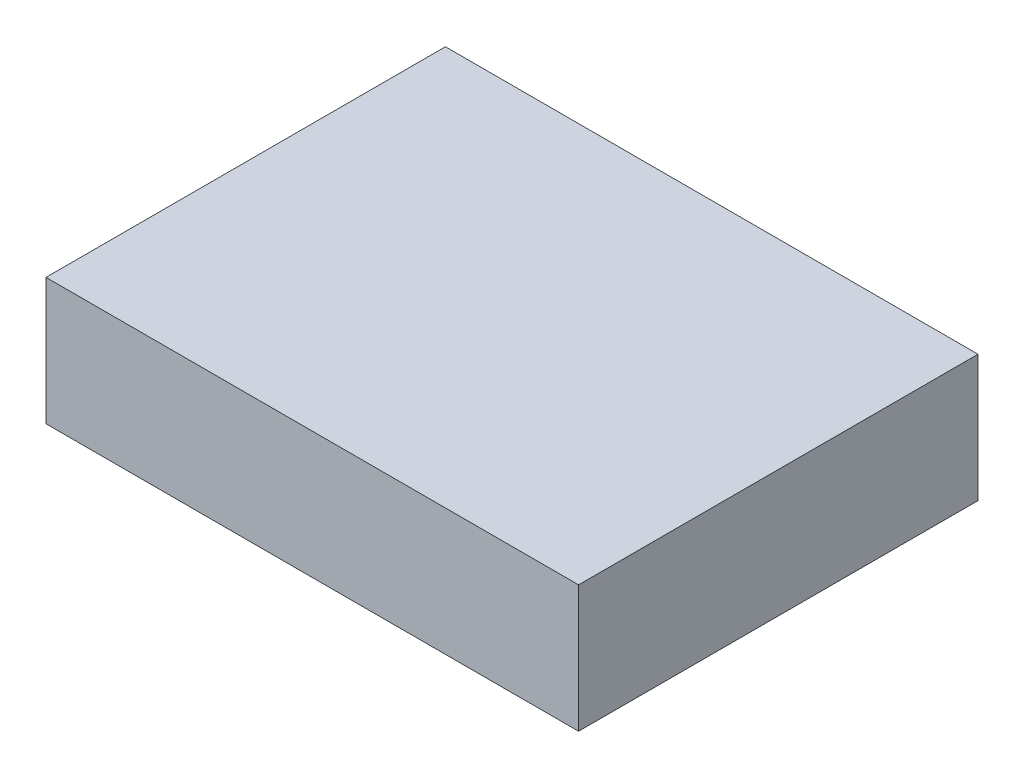
SolidWorks part; units mm, degrees
ref_plane "前视基准面" through (0, 0, 0) normal (0, 0, 1) x (1, 0, 0)
ref_plane "上视基准面" through (0, 0, 0) normal (0, 1, 0) x (1, 0, 0)
ref_plane "右视基准面" through (0, 0, 0) normal (1, 0, 0) x (0, 0, -1)
other "Configuration Table"
sketch "草图1" plane through (0, 0, 0) normal (0, 1, 0) x (1, 0, 0)
  line L1 (0, 0) -> (210, 0)
  line L2 (0, 0) -> (0, 157.5)
  line L3 (0, 157.5) -> (210, 157.5)
  line L4 (210, 0) -> (210, 157.5)
  line L5 (34.0565, 157.5) -> (59.0565, 157.5)
  line L6 (34.0565, 157.5) -> (34.0565, 172.5)
  line L7 (44.0565, 182.5) -> (49.0565, 182.5)
  line L8 (59.0565, 157.5) -> (59.0565, 172.5)
  line L9 (156.4911, 157.5) -> (181.4911, 157.5)
  line L10 (156.4911, 157.5) -> (156.4911, 172.5)
  line L11 (166.4911, 182.5) -> (171.4911, 182.5)
  line L12 (181.4911, 157.5) -> (181.4911, 172.5)
  arc A0 (171.4911, 182.5) -> (181.4911, 172.5) centre (171.4911, 172.5) cw
  arc A1 (156.4911, 172.5) -> (166.4911, 182.5) centre (166.4911, 172.5) cw
  arc A2 (49.0565, 182.5) -> (59.0565, 172.5) centre (49.0565, 172.5) cw
  arc A3 (34.0565, 172.5) -> (44.0565, 182.5) centre (44.0565, 172.5) cw
  point P15 (181.4911, 182.5)
  point P18 (156.4911, 182.5)
  point P21 (59.0565, 182.5)
  point P24 (34.0565, 182.5)
  dimension "D6" = 10
  dimension "D1" = 210
  dimension "D2" = 25
  dimension "D3" = 25
  dimension "D4" = 25
  dimension "D5" = 25
extrude "凸台-拉伸1" add sketch "草图1" along normal blind 10 contours L1 L4 L3 L2 | A3 L6 L3 L8 A2 L7 | A1 L10 L3 L12 A0 L11
sketch "草图2" plane through (0, 10, 0) normal (0, 1, 0) x (1, 0, 0)
  line L1 (0, 157.5) -> (210, 157.5)
  line L2 (0, 157.5) -> (0, 0)
  line L3 (0, 0) -> (210, 0)
  line L4 (210, 157.5) -> (210, 0)
extrude "凸台-拉伸2" add sketch "草图2" along normal blind 40
sketch "草图3" plane through (0, 10, 0) normal (0, 1, 0) x (1, 0, 0)
  circle A0 centre (46.4812, 172.9384) radius 3.7904
  circle A1 centre (168.2093, 172.9384) radius 3.9515
extrude "切除-拉伸1" cut sketch "草图3" against normal blind 40
